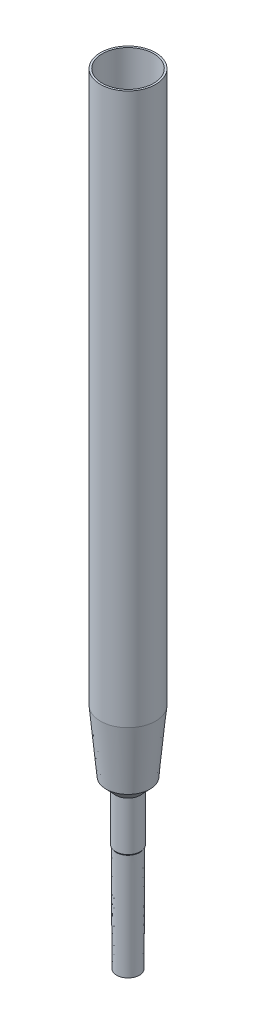
SolidWorks part; units mm, degrees
material "Cast Alloy Steel"
ref_plane "Plane1" through (0, 0, 0) normal (0, 0, 1) x (1, 0, 0)
ref_plane "Plane2" through (0, 0, 0) normal (0, 1, 0) x (1, 0, 0)
ref_plane "Plane3" through (0, 0, 0) normal (1, 0, 0) x (0, 0, -1)
sketch "Sketch1" plane through (0, 0, 0) normal (0, 0, 1) x (1, 0, 0)
  line L0 (0, 0) -> (0, 84.9768) construction
  line L1 (-1, 0) -> (-1.2, 0)
  line L2 (-1.2, 0) -> (-1.25, 16.4)
  line L3 (-1.25, 16.4) -> (-2.3, 17.5)
  line L4 (-2.3, 17.5) -> (-2.9, 24)
  line L5 (-2.9, 24) -> (-2.9, 82)
  line L6 (-2.9, 82) -> (-2.7, 82)
  line L8 (-2.7, 82) -> (-2.7, 24.0092)
  line L9 (-2.7, 24.0092) -> (-2.1072, 17.5877)
  line L10 (-2.1072, 17.5877) -> (-1.0502, 16.4804)
  line L11 (-1.0502, 16.4804) -> (-1, 0)
  point P11 (-6.7362, 19.6216)
  dimension "D1" = 2.4
  dimension "D2" = 0.2
  dimension "D3" = 0.2
  dimension "D4" = 5.8
  dimension "D5" = 1.1
  dimension "D6" = 6.5
  dimension "D7" = 58
  dimension "D8" = 82
  dimension "D9" = 5.274
  dimension "D12" = 0.175
  dimension "D13" = 43.668
  dimension "D14" = 0.2
  dimension "D15" = 0.2
  dimension "D16" = 2.5
revolve "Base-Revolve" add sketch "Sketch1" angle 360 about L0
sketch "Esboço1" plane through (0, 0, 0) normal (0, 0, 1) x (1, 0, 0)
  line L0 (-1.2341, 11.2) -> (-1.3, 11.3141)
  line L1 (-1.25, 16.4) -> (-1.2, 0) construction
  line L2 (-1.3, 11.3141) -> (-1.3, 16.4524)
  line L3 (-2.3, 17.5) -> (-1.25, 16.4) construction
  line L4 (-1.25, 16.4) -> (-1.2341, 11.2)
  line L5 (-1.3, 16.4524) -> (-1.25, 16.4)
  line L6 (0, 0) -> (0, 21.6169) construction
  line L7 (-1.2, 0) -> (1.2, 0) construction
  dimension "D1" = 30
  dimension "D2" = 11.2
  dimension "D3" = 2.6
revolve "Revolução1" add sketch "Esboço1" angle 360 about L6
